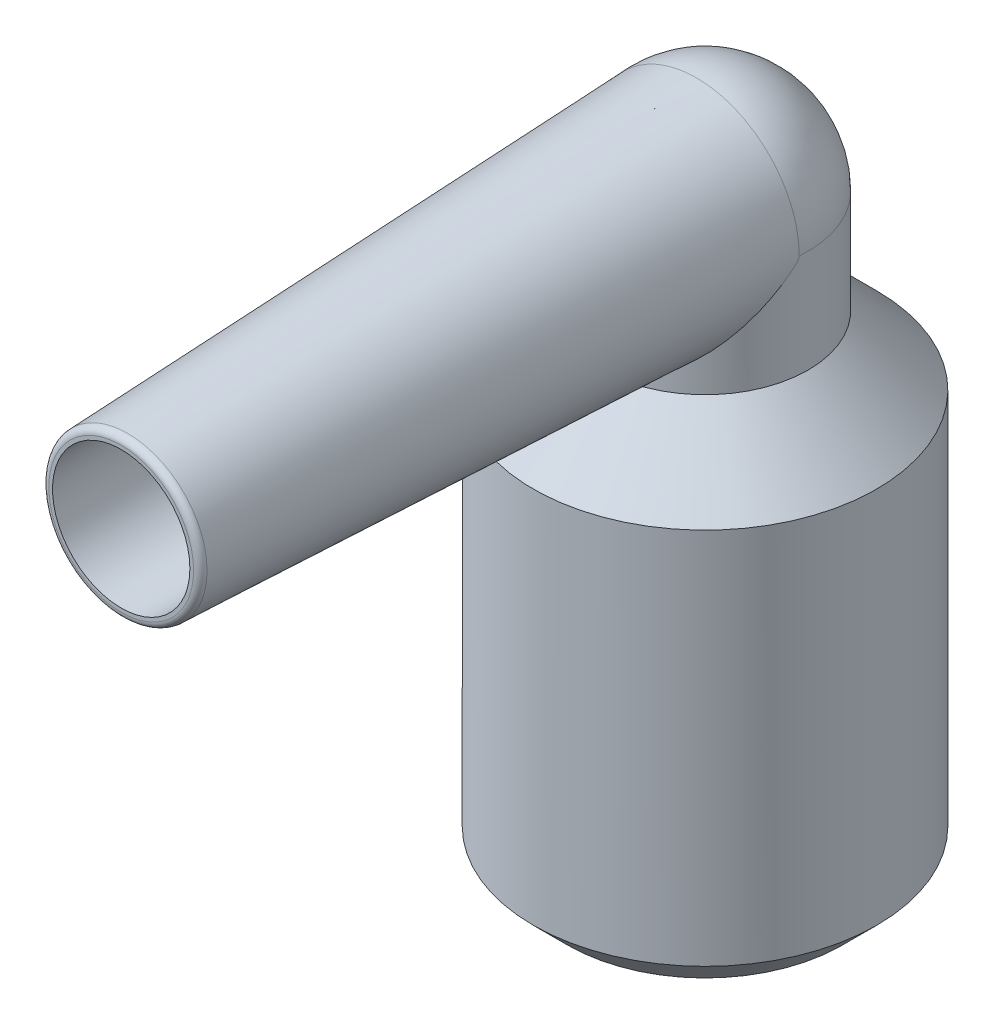
SolidWorks part; units mm, degrees
ref_plane "前视基准面" through (0, 0, 0) normal (0, 0, 1) x (1, 0, 0)
ref_plane "上视基准面" through (0, 0, 0) normal (0, 1, 0) x (1, 0, 0)
ref_plane "右视基准面" through (0, 0, 0) normal (1, 0, 0) x (0, 0, -1)
sketch "草图1" plane through (0, 0, 0) normal (0, 1, 0) x (1, 0, 0)
  circle A0 centre (0, 0) radius 2.5
  dimension "D1" = 5
extrude "凸台-拉伸1" add sketch "草图1" along normal blind 6
sketch "草图2" plane through (0, 6, 0) normal (0, 1, 0) x (1, 0, 0)
  line L0 (0, 0) -> (-2.5, 0) construction
  circle A1 centre (0, 0) radius 2.5
  circle A2 centre (0, 0) radius 2.5
  dimension "D1" = 0
ref_plane "基准面1" through (0, 7, 0) normal (0, 1, 0) x (1, 0, 0)
sketch "草图3" plane through (0, 7, 0) normal (0, 1, 0) x (1, 0, 0)
  line L0 (0, 0) -> (-1.5, 0) construction
  circle A0 centre (0, 0) radius 1.5
  dimension "D1" = 3
loft "放样1" add profiles "草图2", "草图3"
sketch "草图4" plane through (0, 0, 0) normal (0, 0, 1) x (1, 0, 0)
  line L0 (0, 7) -> (0, 8.5)
  line L1 (1.5, 7) -> (-1.5, 7) construction
  line L2 (-1.5, 7) -> (-1.5, 8.5)
  line L3 (0, 8.5) -> (0, 10)
  line L4 (-1.5, 7) -> (0, 7)
  arc A0 (0, 10) -> (-1.5, 8.5) centre (0, 8.5) ccw
  dimension "D1" = 1.5
revolve "旋转1" add sketch "草图4" angle 360 about L3
sketch "草图5" plane through (0, 0, 0) normal (0, 0, 1) x (1, 0, 0)
  line L0 (0, 0) -> (0, 8.5) construction
  line L1 (0, 8.5) -> (-1.5, 8.5) construction
  circle A0 centre (0, 8.5) radius 1.5
  dimension "D2" = 3
  dimension "D1" = 8.5
ref_plane "基准面2" through (0, 0, 8.5) normal (0, 0, 1) x (1, 0, 0)
sketch "草图6" plane through (0, 0, 8.5) normal (0, 0, 1) x (1, 0, 0)
  line L0 (0, 8.5) -> (-1.15, 8.5) construction
  circle A0 centre (0, 8.5) radius 1.15
  dimension "D1" = 2.3
loft "放样2" add profiles "草图5", "草图6"
sketch "草图7" plane through (0, 0, 8.5) normal (0, 0, 1) x (1, 0, 0)
  circle A0 centre (0, 8.5) radius 1
  dimension "D1" = 2
extrude "切除-拉伸1" cut sketch "草图7" against normal blind 8.5
sketch "草图8" plane through (0, 0, 0) normal (0, -1, 0) x (1, 0, 0)
  circle A0 centre (0, 0) radius 1.25
  dimension "D1" = 2.5
extrude "切除-拉伸2" cut sketch "草图8" against normal blind 8.5
chamfer "倒角1" distance 0.5 angle 45 2 edges at (0, 0, 2.5) (0, 0, -1.25)
fillet "圆角1" radius 0.1 1 edges at (1.15, 8.5, 8.5)
